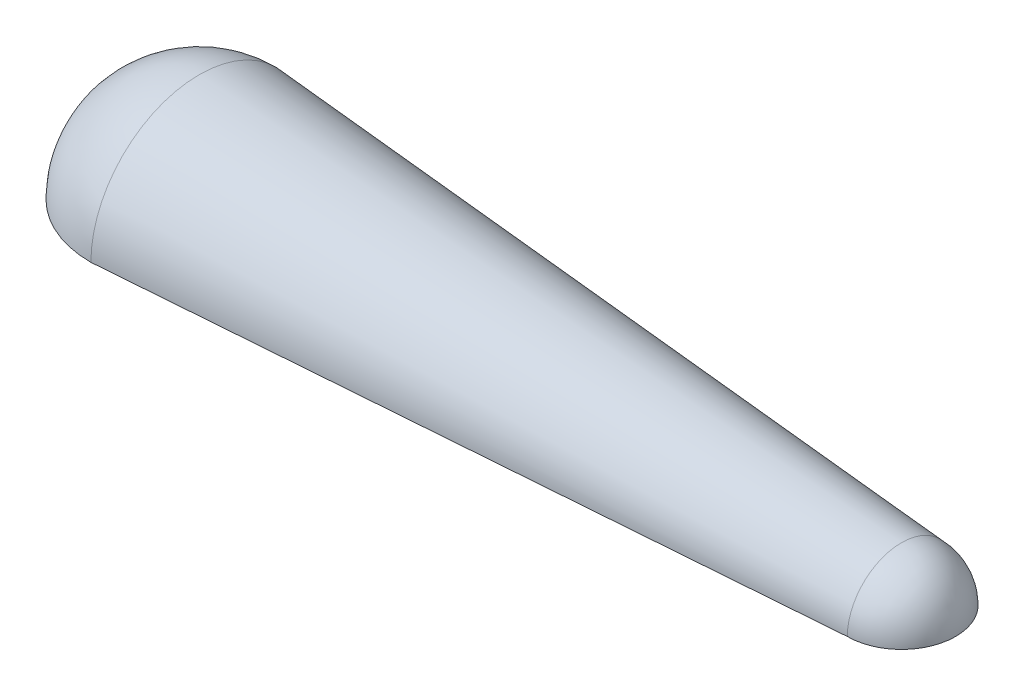
SolidWorks part; units mm, degrees
ref_plane "Front Plane" through (0, 0, 0) normal (0, 0, 1) x (1, 0, 0)
ref_plane "Top Plane" through (0, 0, 0) normal (0, 1, 0) x (1, 0, 0)
ref_plane "Right Plane" through (0, 0, 0) normal (1, 0, 0) x (0, 0, -1)
sketch "Sketch1" plane through (0, 0, 0) normal (0, 1, 0) x (1, 0, 0)
  line L0 (0, 18.517) -> (120, 9.2585)
  line L2 (0, 14) -> (120, 6)
  line L3 (-18.517, 0) -> (129.2585, 0) construction
  line L4 (-18.517, 0) -> (-14, 0)
  line L5 (126, 0) -> (129.2585, 0)
  arc A0 (0, 18.517) -> (-18.517, 0) centre (0, 0) ccw
  arc A1 (129.2585, 0) -> (120, 9.2585) centre (120, 0) ccw
  arc A4 (0, 14) -> (-14, 0) centre (0, 0) ccw
  arc A5 (126, 0) -> (120, 6) centre (120, 0) ccw
  dimension "D1" = 120
revolve "Revolve1" add sketch "Sketch1" angle 180 about L3
sketch "Sketch3" plane through (0, 0, 0) normal (0, -1, 0) x (1, 0, 0)
  line L0 (120, 6) -> (120, -6) construction
  circle A0 centre (-16, 0) radius 1
  circle A1 centre (0, 16) radius 1
  circle A2 centre (0, -16) radius 1
  circle A3 centre (127.5, 0) radius 1
  point P12 (120, 0)
  dimension "D1" = 16
  dimension "D2" = 16
  dimension "D3" = 16
  dimension "D4" = 7.5
  dimension "D5" = 127.5
extrude "Cut-Extrude1" cut sketch "Sketch3" against normal blind 2.5
